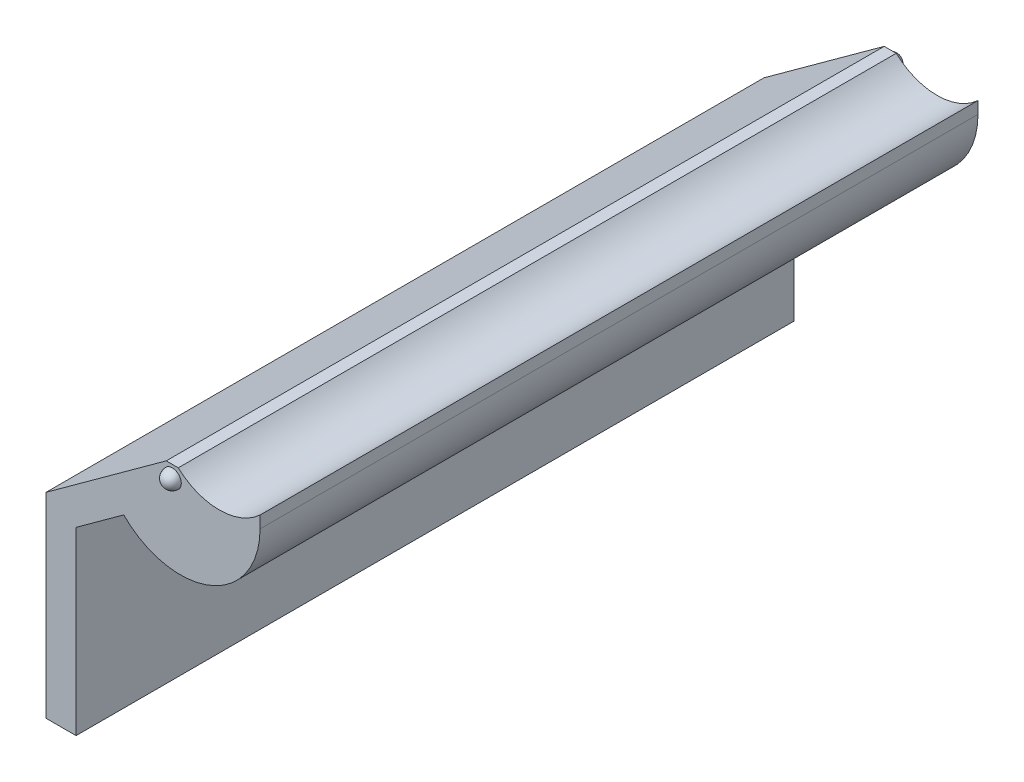
SolidWorks part; units mm, degrees
ref_plane "Front Plane" through (0, 0, 0) normal (0, 0, 1) x (1, 0, 0)
ref_plane "Top Plane" through (0, 0, 0) normal (0, 1, 0) x (1, 0, 0)
ref_plane "Right Plane" through (0, 0, 0) normal (1, 0, 0) x (0, 0, -1)
sketch "Sketch1" plane through (0, 0, 0) normal (0, 0, 1) x (1, 0, 0)
  line L0 (-19.05, -41.4676) -> (-8.9818, -34.1526)
  line L2 (-25.4, -38.2321) -> (-25.4, -79.5676)
  line L3 (-25.4, -79.5676) -> (-19.05, -79.5676)
  line L4 (-19.05, -41.4676) -> (-19.05, -79.5676)
  line L5 (-25.4, -38.2321) -> (0, -19.7779)
  line L6 (19.812, -19.7779) -> (19.812, -22.3179)
  line L7 (0, -38.8805) -> (0, -150.6026) construction
  line L9 (0, 29.1888) -> (0, -19.7779) construction
  line L11 (0, -19.7779) -> (2.54, -19.7779)
  arc A0 (-8.9818, -34.1526) -> (19.812, -22.3179) centre (2.983, -22.3179) ccw
  arc A1 (2.54, -19.7779) -> (19.812, -19.7779) centre (11.176, -10.4661) ccw
  dimension "D9" = 12.7
  dimension "D1" = 6.35
  dimension "D2" = 6.35
  dimension "D3" = 2.54
  dimension "D4" = 126
  dimension "D5" = 19.05
  dimension "D6" = 38.1
  dimension "D7" = 19.812
  dimension "D8" = 2.54
extrude "Boss-Extrude1" add sketch "Sketch1" along normal mid plane 151.638
sketch "Sketch2" plane through (0, 0, 75.819) normal (0, 0, 1) x (1, 0, 0)
  line L0 (2.54, -19.7779) -> (0, -19.7779) construction
  line L2 (1.27, -20.4129) -> (1.27, -24.2229)
  arc A0 (1.27, -24.2229) -> (1.27, -20.4129) centre (1.27, -22.3179) ccw
  point P4 (1.27, -19.7779)
  dimension "D1" = 3.81
revolve "Revolve1" add sketch "Sketch2" angle 360 about L2
sketch "Sketch3" plane through (0, 0, -75.819) normal (0, 0, -1) x (-1, 0, 0)
  line L0 (-1.27, -20.4129) -> (-1.27, -24.2229)
  arc A0 (-1.27, -24.2229) -> (-1.27, -20.4129) centre (-1.27, -22.3179) ccw
  circle A1 centre (-1.27, -22.3179) radius 1.905 construction
revolve "Revolve2" add sketch "Sketch3" angle 360 about L0
